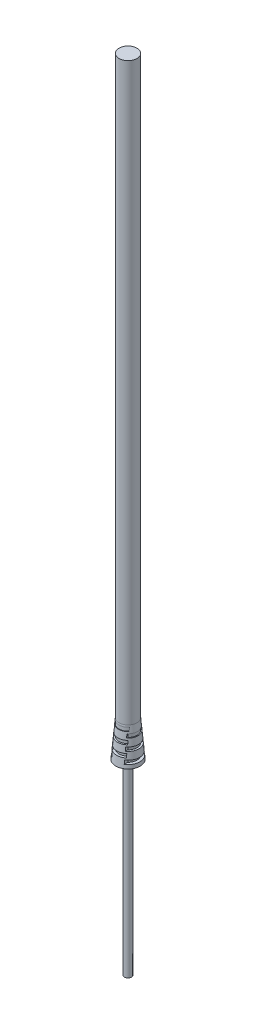
SolidWorks part; units mm, degrees
material "Silicon Rubber"
ref_plane "Front Plane" through (0, 0, 0) normal (0, 0, 1) x (1, 0, 0)
ref_plane "Top Plane" through (0, 0, 0) normal (0, 1, 0) x (1, 0, 0)
ref_plane "Right Plane" through (0, 0, 0) normal (1, 0, 0) x (0, 0, -1)
sketch "Sketch2" plane through (0, 0, 0) normal (0, 1, 0) x (1, 0, 0)
  circle A0 centre (0, 0) radius 1.25
  dimension "D1" = 2.5
extrude "Boss-Extrude1" add sketch "Sketch2" along normal blind 80
sketch "Sketch3" plane through (0, 0, 0) normal (0, -1, 0) x (1, 0, 0)
  circle A0 centre (0, 0) radius 1.25
  dimension "D1" = 2.5
extrude "Boss-Extrude2" add sketch "Sketch3" along normal blind 5 draft 5 draft outward yes
sketch "Sketch4" plane through (0, -5, 0) normal (0, -1, 0) x (1, 0, 0)
  line L0 (-2.037, 0) -> (1.8937, 0) construction
  line L9 (0, 1.7281) -> (0, -1.8265) construction
  line L10 (-0.87, 1.4459) -> (-0.87, 0.8976)
  line L11 (-2.4947, 1.4459) -> (-0.87, 1.4459)
  line L12 (-2.4947, 1.4459) -> (-2.4947, -1.4459)
  line L13 (-2.4947, -1.4459) -> (-0.87, -1.4459)
  line L14 (1.9553, 1.4459) -> (1.9553, -1.4459)
  line L15 (-0.87, -0.8976) -> (-0.87, -1.4459)
  line L16 (0.87, 1.4459) -> (0.87, 0.8976)
  line L17 (0.87, -0.8976) -> (0.87, -1.4459)
  line L18 (0.87, 1.4459) -> (1.9553, 1.4459)
  line L19 (0.87, -1.4459) -> (1.9553, -1.4459)
  circle A0 centre (0, 0) radius 1.25
  circle A1 centre (0, 0) radius 1.6874 construction
  arc A2 (-0.87, 0.8976) -> (-0.87, -0.8976) centre (0, 0) ccw
  arc A3 (0.87, 0.8976) -> (0.87, -0.8976) centre (0, 0) cw
  circle M22 centre (0, 0) radius 1.6874
  dimension "D1" = 2.5
  dimension "D2" = 0.87
extrude "Cut-Extrude3" cut sketch "Sketch4" against normal blind 0.5 from offset 0.5 contours A0 L10 L15 M22 | A0 L17 L16 M22 offset against normal yes
pattern_linear "LPattern1" count 3 spacing 1.5 along (0, 1, 0) of "Cut-Extrude3"
sketch "Sketch6" plane through (0, -5, 0) normal (0, -1, 0) x (1, 0, 0)
  line L0 (0, 2.1054) -> (0, -1.9491) construction
  line L1 (-1.9926, 0) -> (2.0619, 0) construction
  line L2 (-1, -0.75) -> (-1, -2.3428)
  line L3 (-1, 2.3428) -> (1, 2.3428)
  line L4 (-1, 2.3428) -> (-1, 0.75)
  line L5 (-1, -2.3428) -> (1, -2.3428)
  line L6 (1, 2.3428) -> (1, 0.75)
  line L7 (1, -0.75) -> (1, -2.3428)
  circle A0 centre (0, 0) radius 1.25
  arc A1 (-1, 0.75) -> (1, 0.75) centre (0, 0) cw
  arc A2 (-1, -0.75) -> (1, -0.75) centre (0, 0) ccw
  circle M8 centre (0, 0) radius 1.6874
  dimension "D1" = 2.5
  dimension "D2" = 0.75
extrude "Cut-Extrude4" cut sketch "Sketch6" against normal blind 0.5 from offset 1.25 contours A0 L6 L4 M8 | A0 L2 L7 M8 offset against normal yes
pattern_linear "LPattern2" count 3 spacing 1.5 along (0, 1, 0) of "Cut-Extrude4"
sketch "Sketch7" plane through (0, -5, 0) normal (0, -1, 0) x (1, 0, 0)
  circle A0 centre (0, 0) radius 0.5
  dimension "D1" = 1
extrude "Boss-Extrude3" add sketch "Sketch7" along normal blind 26
